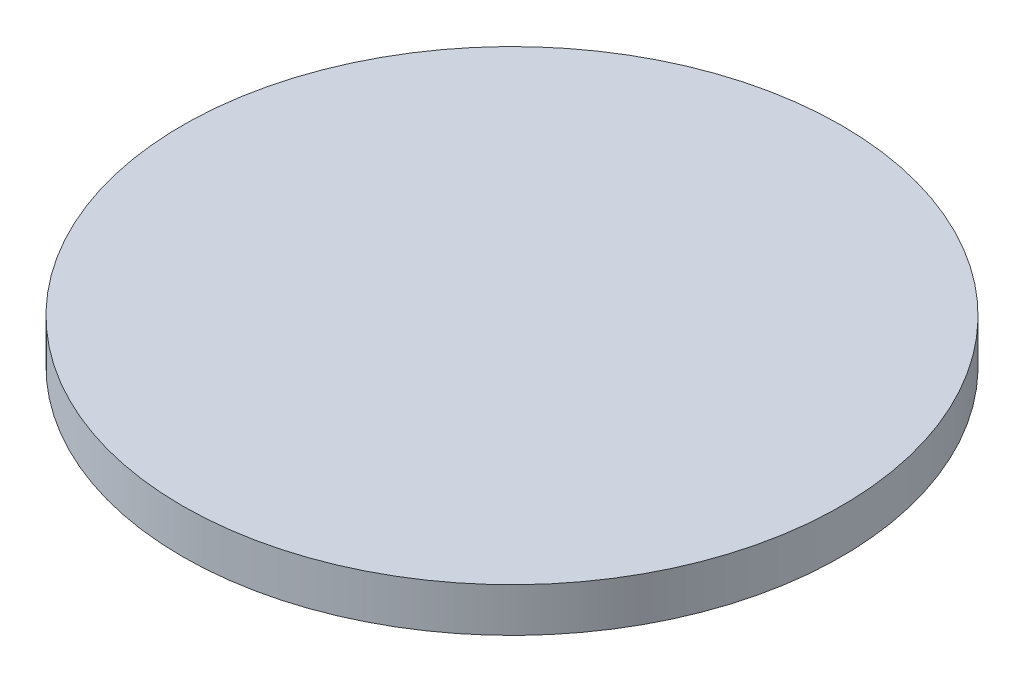
SolidWorks part; units mm, degrees
material "黄铜"
ref_plane "前视基准面" through (0, 0, 0) normal (0, 0, 1) x (1, 0, 0)
ref_plane "上视基准面" through (0, 0, 0) normal (0, 1, 0) x (1, 0, 0)
ref_plane "右视基准面" through (0, 0, 0) normal (1, 0, 0) x (0, 0, -1)
other "Configuration Table"
sketch "草图1" plane through (0, 0, 0) normal (0, 1, 0) x (1, 0, 0)
  circle A0 centre (0, 0) radius 15
  dimension "D1" = 30
extrude "凸台-拉伸1" add sketch "草图1" along normal blind 2
